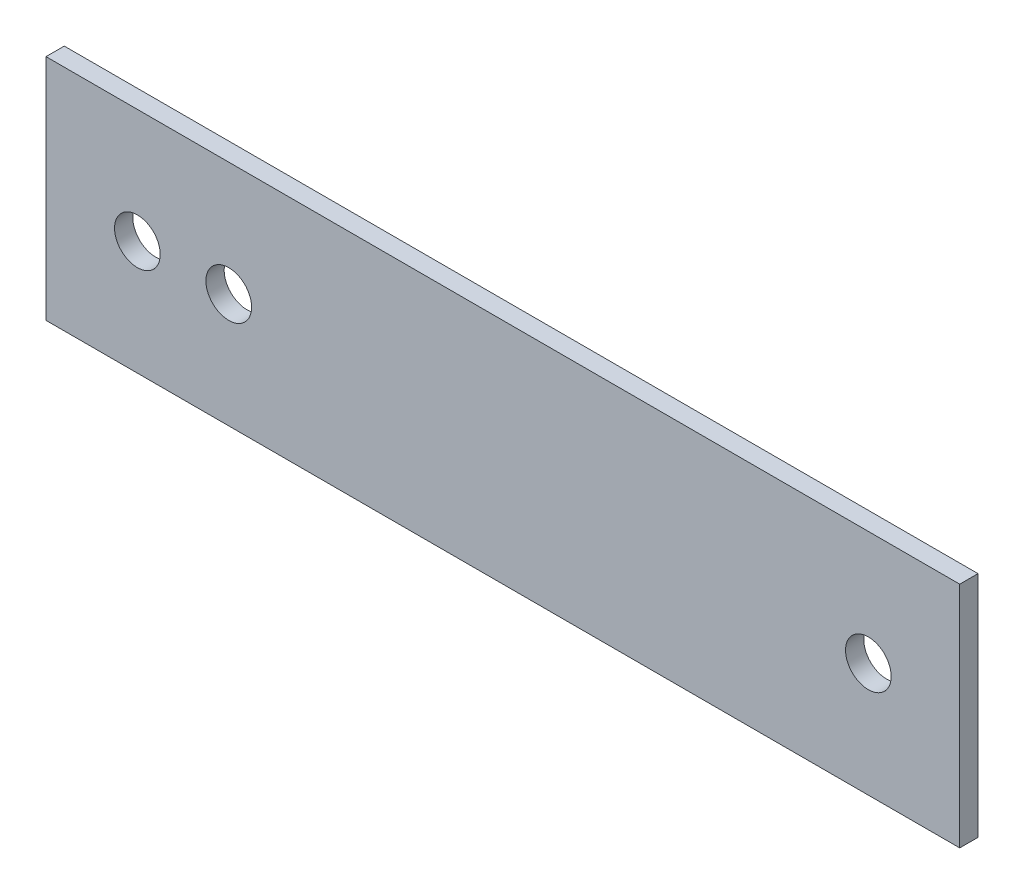
SolidWorks part; units mm, degrees
ref_plane "Plano frontal" through (0, 0, 0) normal (0, 0, 1) x (1, 0, 0)
ref_plane "Plano superior" through (0, 0, 0) normal (0, 1, 0) x (1, 0, 0)
ref_plane "Plano direito" through (0, 0, 0) normal (1, 0, 0) x (0, 0, -1)
sketch "Esboço1" plane through (0, 0, 0) normal (0, 0, 1) x (1, 0, 0)
  line L1 (-28.8896, 9.6955) -> (71.1104, 9.6955)
  line L2 (-28.8896, 9.6955) -> (-28.8896, -15.3045)
  line L3 (-28.8896, -15.3045) -> (71.1104, -15.3045)
  line L4 (71.1104, 9.6955) -> (71.1104, -15.3045)
  circle A0 centre (-18.8896, -2.8045) radius 2.5
  circle A1 centre (-8.8896, -2.8045) radius 2.5
  circle A2 centre (61.1104, -2.8045) radius 2.5
  dimension "D3" = 5
  dimension "D4" = 5
  dimension "D5" = 10
  dimension "D6" = 10
  dimension "D7" = 10
  dimension "D8" = 5
  dimension "D1" = 25
  dimension "D2" = 100
extrude "Ressalto-extrusão1" add sketch "Esboço1" along normal blind 2
